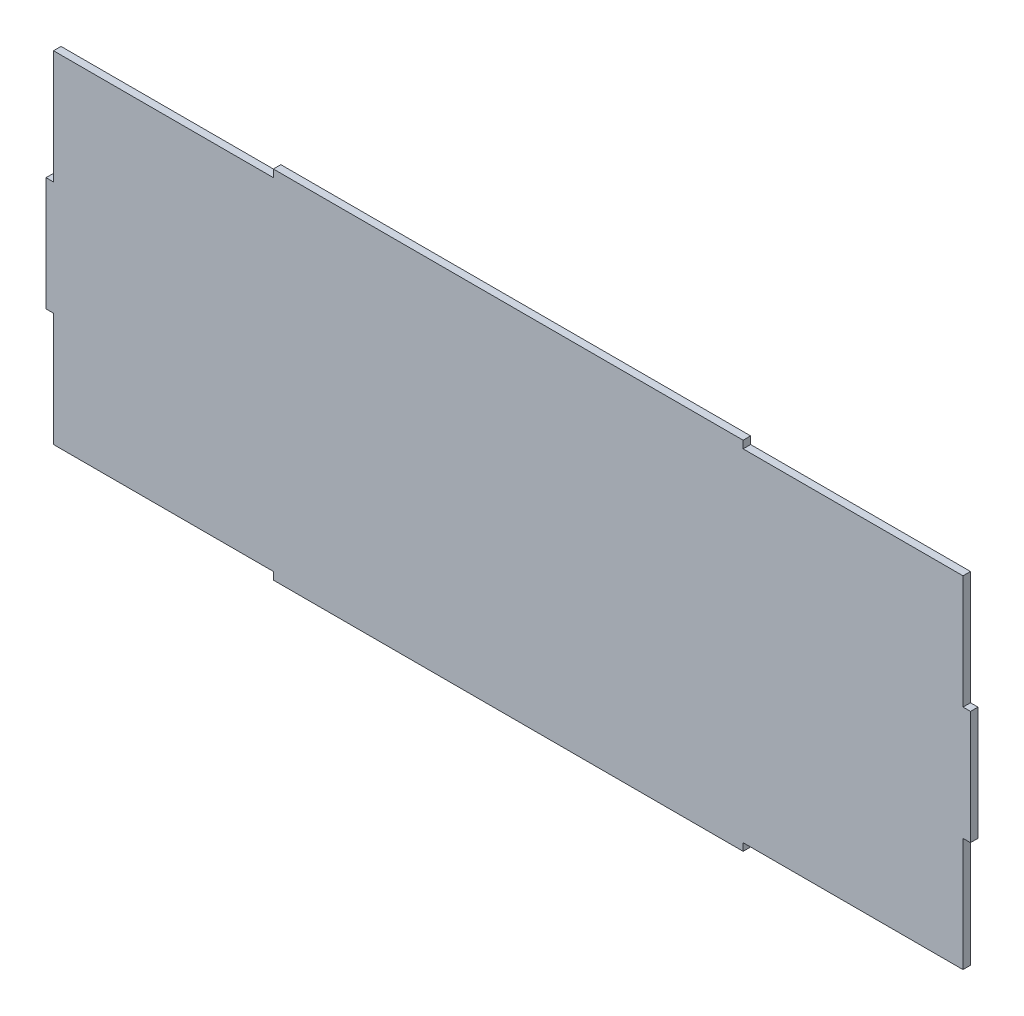
SolidWorks part; units mm, degrees
ref_plane "Alzado" through (0, 0, 0) normal (0, 0, 1) x (1, 0, 0)
ref_plane "Planta" through (0, 0, 0) normal (0, 1, 0) x (1, 0, 0)
ref_plane "Vista lateral" through (0, 0, 0) normal (1, 0, 0) x (0, 0, -1)
sketch "Croquis1" plane through (0, 0, 0) normal (0, 0, 1) x (1, 0, 0)
  line L0 (-203.3, 25) -> (-203.3, -25)
  line L2 (-200, 75) -> (-200, 25)
  line L3 (-200, 25) -> (-203.3, 25)
  line L5 (-203.3, -25) -> (-200, -25)
  line L8 (-200, -25) -> (-200, -75)
  line L9 (-200, 75) -> (-103.3, 75)
  line L13 (103.3, 75) -> (200, 75)
  line L14 (200, 75) -> (200, 25)
  line L15 (200, 25) -> (203.3, 25)
  line L16 (203.3, 25) -> (203.3, -25)
  line L17 (203.3, -25) -> (200, -25)
  line L18 (200, -25) -> (200, -75)
  line L19 (200, -75) -> (103.3, -75)
  line L20 (103.3, -75) -> (103.3, -78.3)
  line L21 (103.3, -78.3) -> (-103.3, -78.3)
  line L22 (-103.3, -78.3) -> (-103.3, -75)
  line L23 (-103.3, -75) -> (-200, -75)
  line L24 (-103.3, 78.3) -> (103.3, 78.3)
  line L25 (103.3, 78.3) -> (103.3, 75)
  line L26 (-103.3, 78.3) -> (-103.3, 75)
  point P3 (0, -78.3)
  point P6 (203.3, 0)
  dimension "D1" = 3.3
  dimension "D2" = 406.6
  dimension "D3" = 150
  dimension "D4" = 96.7
  dimension "D5" = 96.7
extrude "Saliente-Extruir1" add sketch "Croquis1" along normal blind 3.3
